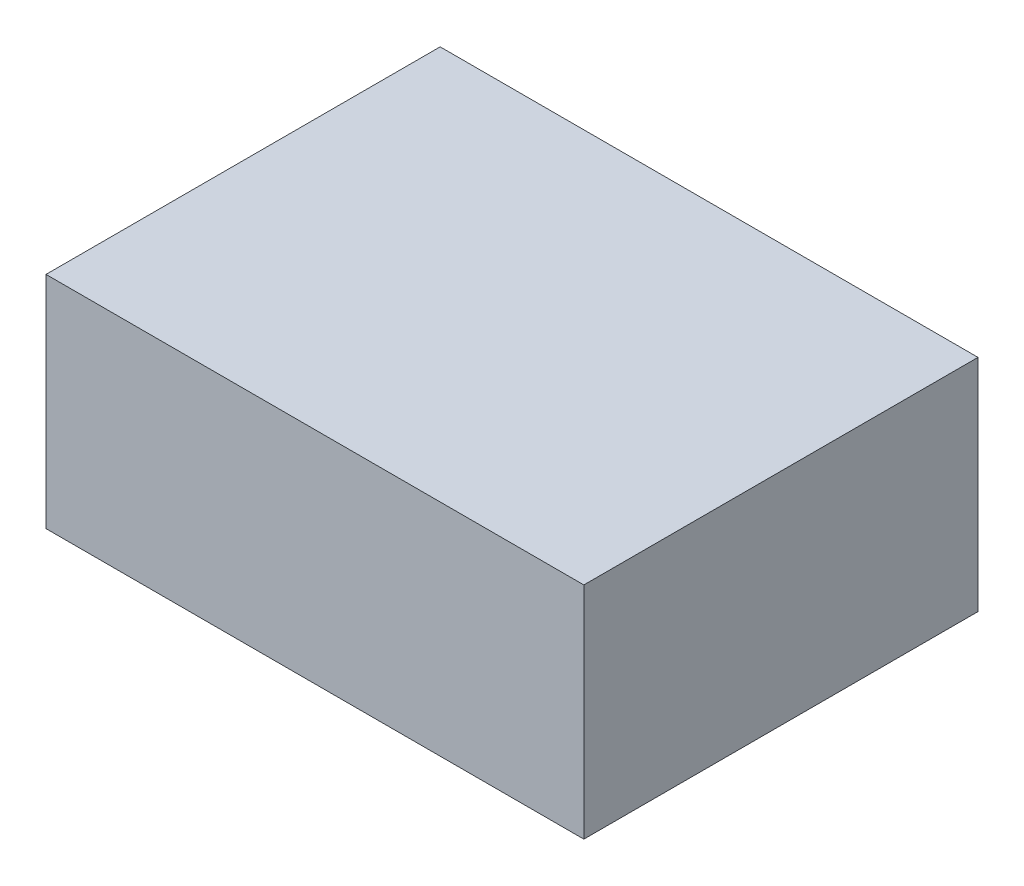
SolidWorks part; units mm, degrees
ref_plane "Front Plane" through (0, 0, 0) normal (0, 0, 1) x (1, 0, 0)
ref_plane "Top Plane" through (0, 0, 0) normal (0, 1, 0) x (1, 0, 0)
ref_plane "Right Plane" through (0, 0, 0) normal (1, 0, 0) x (0, 0, -1)
sketch "Sketch1" plane through (0, 0, 0) normal (0, 0, 1) x (1, 0, 0)
  line L1 (-32, -13.1) -> (32, -13.1)
  line L2 (-32, -13.1) -> (-32, 13.1)
  line L3 (-32, 13.1) -> (32, 13.1)
  line L4 (32, -13.1) -> (32, 13.1)
  line L5 (-32, -13.1) -> (32, 13.1) construction
  line L6 (-32, 13.1) -> (32, -13.1) construction
  point P0 (0, 0)
extrude "Envelope" add sketch "Sketch1" along normal blind 46.9
